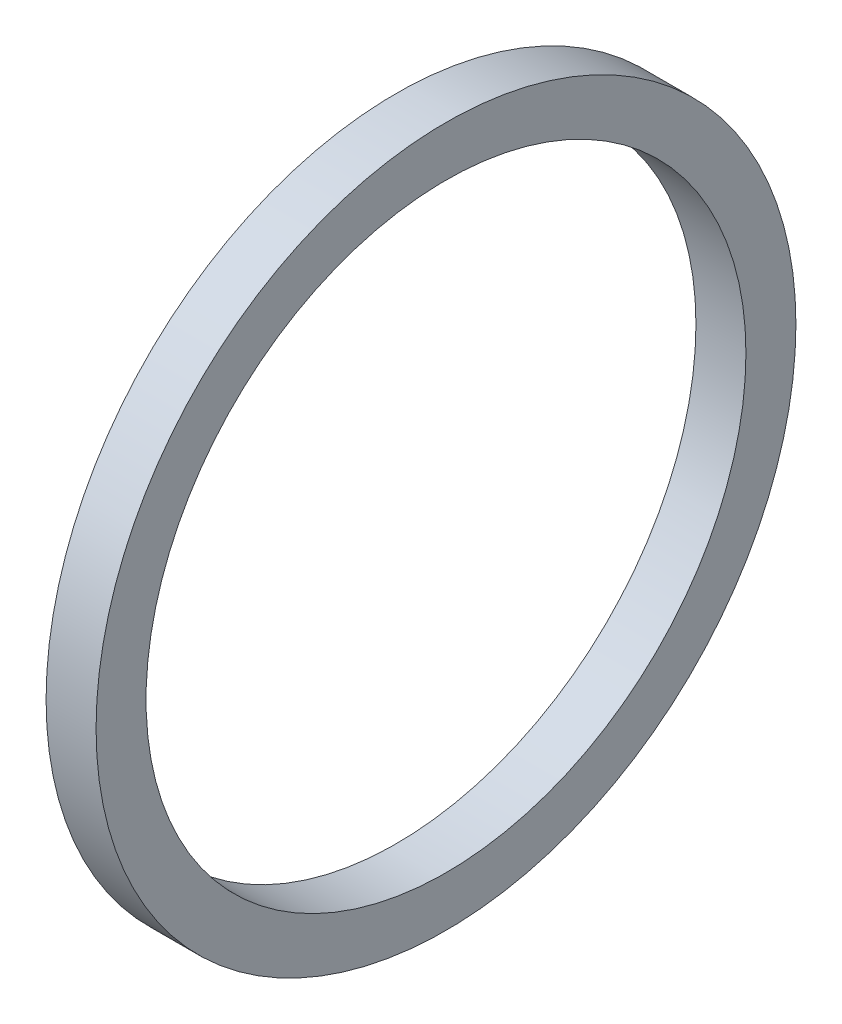
SolidWorks part; units mm, degrees
ref_plane "Front Plane" through (0, 0, 0) normal (0, 0, 1) x (1, 0, 0)
ref_plane "Top Plane" through (0, 0, 0) normal (0, 1, 0) x (1, 0, 0)
ref_plane "Right Plane" through (0, 0, 0) normal (1, 0, 0) x (0, 0, -1)
sketch "Sketch1" plane through (0, 0, 0) normal (0, 0, 1) x (1, 0, 0)
  line L0 (0, 0) -> (0, 76.2) construction
  line L1 (0, 0) -> (-79.1077, 0) construction
  line L2 (0, 76.2) -> (-12.7, 76.2)
  line L3 (0, 76.2) -> (0, 88.9)
  line L4 (0, 88.9) -> (-12.7, 88.9)
  line L5 (-12.7, 76.2) -> (-12.7, 88.9)
  dimension "D1" = 12.7
  dimension "D2" = 12.7
  dimension "D3" = 76.2
revolve "Revolve1" add sketch "Sketch1" angle 360 about L1
